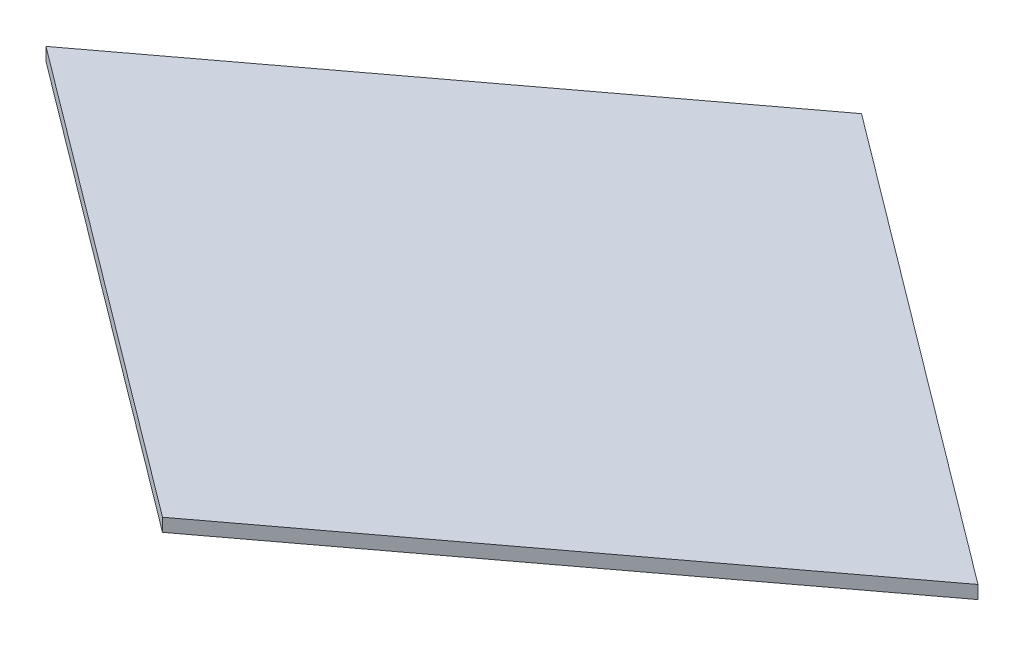
SolidWorks part; units mm, degrees
ref_plane "Front Plane" through (0, 0, 0) normal (0, 0, 1) x (1, 0, 0)
ref_plane "Top Plane" through (0, 0, 0) normal (0, 1, 0) x (1, 0, 0)
ref_plane "Right Plane" through (0, 0, 0) normal (1, 0, 0) x (0, 0, -1)
sketch "Sketch1" plane through (0, 0, 0) normal (0, 1, 0) x (1, 0, 0)
  line L20 (0, 150) -> (200, 0)
  line L21 (200, 0) -> (0, -150)
  line L22 (0, -150) -> (-200, 0)
  line L23 (-200, 0) -> (0, 150)
  point P4 (0, 0)
  point P5 (0, 0)
  dimension "D1" = 400
  dimension "D3" = 300
  dimension "D2" = 200
extrude "Boss-Extrude1" add sketch "Sketch1" along normal blind 5.63
equation "\"Side\"= 170.5"
equation "\"thick acrylic\"= 5.63"
equation "\"connect width\"= 15"
equation "\"thin acrylic\"= 2.95"
equation "\"width\"= 300"
equation "\"length\"= 400"
equation "\"D1@Boss-Extrude1\"=\"thick acrylic\""
equation "\"D1@Sketch1\"=\"length\""
equation "\"D3@Sketch1\"=\"width\""
equation "\"D2@Sketch1\"=\"length\"/2"
